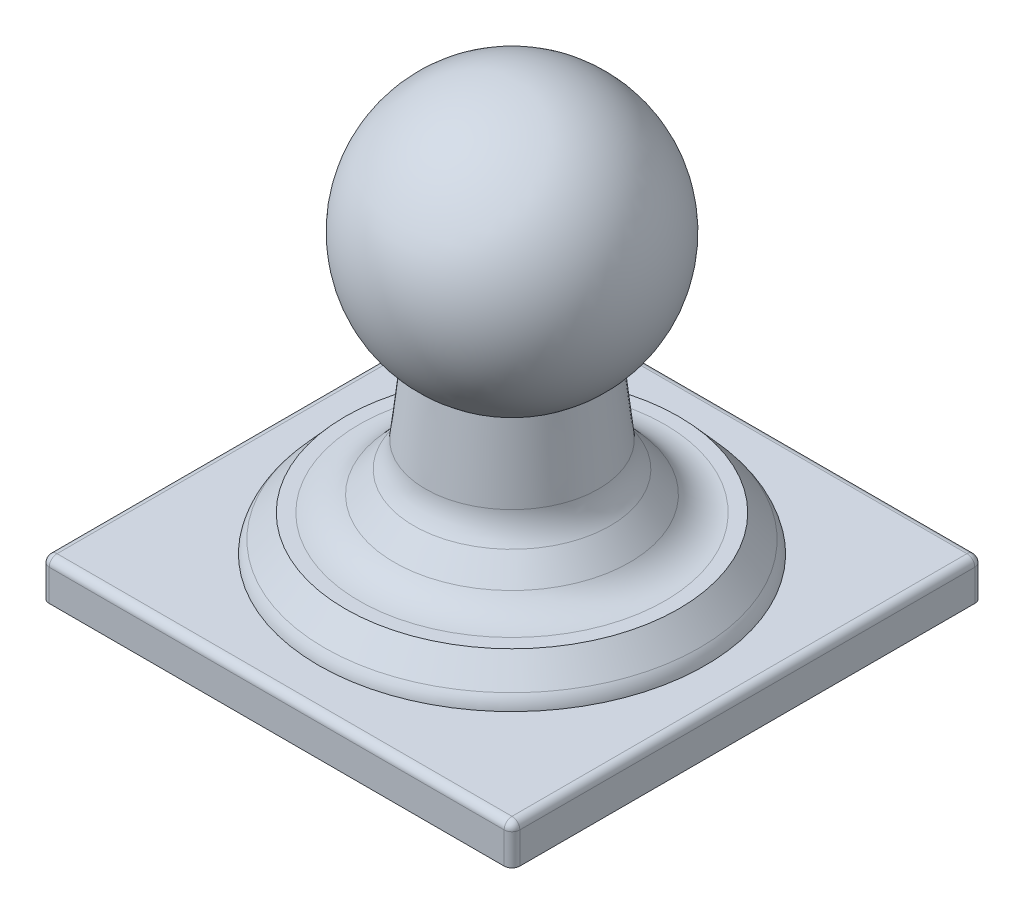
SolidWorks part; units mm, degrees
ref_plane "Front Plane" through (0, 0, 0) normal (0, 0, 1) x (1, 0, 0)
ref_plane "Top Plane" through (0, 0, 0) normal (0, 1, 0) x (1, 0, 0)
ref_plane "Right Plane" through (0, 0, 0) normal (1, 0, 0) x (0, 0, -1)
sketch "Sketch1" plane through (0, 0, 0) normal (1, 0, 0) x (0, 0, -1)
  line L0 (0, 14.5542) -> (0, -14.5542)
  line L1 (5.08, -0.7952) -> (5.715, -6.5483)
  line L2 (5.715, -6.5483) -> (8.5327, -9.7155)
  line L3 (8.5327, -9.7155) -> (10.7965, -9.7155)
  line L4 (10.7965, -9.7155) -> (12.5603, -11.6981)
  line L5 (12.5603, -11.6981) -> (12.5603, -14.5542)
  line L6 (12.5603, -14.5542) -> (0, -14.5542)
  arc A0 (0, 14.5542) -> (5.08, -0.7952) centre (0, 6.0388) cw
  point P5 (0, 0)
  dimension "D1" = 8.5153
  dimension "D2" = 29.1084
  dimension "D3" = 12.5603
  dimension "D4" = 5.08
  dimension "D5" = 5.715
  dimension "D6" = 5.7531
  dimension "D7" = 4.8387
revolve "Revolve1" add sketch "Sketch1" angle 360 about L0
fillet "Fillet1" radius 1.651 2 edges at (0, -14.5542, 12.5603) (0, -11.6981, 12.5603)
fillet "Fillet2" radius 3.048 2 edges at (0, -9.7155, 8.5327) (0, -6.5483, 5.715)
sketch "Sketch2" plane through (0, -14.5542, 0) normal (0, -1, 0) x (1, 0, 0)
  line L0 (15.24, 15.24) -> (-15.24, -15.24) construction
  line L1 (-15.24, 15.24) -> (15.24, 15.24)
  line L2 (-15.24, 15.24) -> (-15.24, -15.24)
  line L3 (-15.24, -15.24) -> (15.24, -15.24)
  line L4 (15.24, 15.24) -> (15.24, -15.24)
  dimension "D1" = 30.48
extrude "Boss-Extrude1" add sketch "Sketch2" against normal blind 2.54
fillet "Fillet3" radius 0.508 8 edges at (0, -12.0142, -15.24) (15.24, -12.0142, 0) (0, -12.0142, 15.24) (-15.24, -12.0142, 0) (-15.24, -13.2842, -15.24) (-15.24, -13.2842, 15.24) (15.24, -13.2842, -15.24) (15.24, -13.2842, 15.24)
